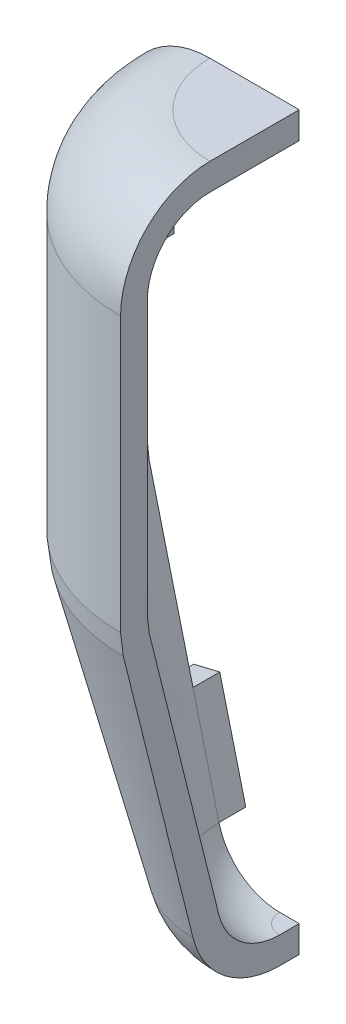
SolidWorks part; units mm, degrees
ref_plane "Front Plane" through (0, 0, 0) normal (0, 0, 1) x (1, 0, 0)
ref_plane "Top Plane" through (0, 0, 0) normal (0, 1, 0) x (1, 0, 0)
ref_plane "Right Plane" through (0, 0, 0) normal (1, 0, 0) x (0, 0, -1)
sketch "Sketch1" plane through (0, 0, 0) normal (0, 0, 1) x (1, 0, 0)
  line L0 (-55.7937, -33.3754) -> (-63.6014, -2.1443)
  line L1 (-63.9, 0.2811) -> (-63.9, 30.95)
  line L2 (-63.9, 30.95) -> (-60.9, 30.95) construction
  line L3 (-63.6014, -2.1443) -> (-63.9, 0.2811)
  line L5 (-53.9, 40.95) -> (-43.9, 40.95)
  line L6 (53.9, 40.95) -> (-53.9, 40.95) construction
  line L7 (-43.9, 40.95) -> (-43.9, 37.95)
  line L8 (-55.7937, -21.006) -> (-52.8832, -32.6477) construction
  line L9 (-52.8832, -32.6477) -> (-55.7937, -21.006)
  line L10 (-55.7937, -21.006) -> (-60.691, -1.4167)
  line L11 (-43.9, 37.95) -> (-53.9, 37.95)
  line L12 (-60.9, 30.95) -> (-60.9, 0.2811)
  line L13 (-60.9, 0.2811) -> (-60.691, -1.4167)
  line L14 (-43.9, -40.95) -> (-46.0922, -40.95)
  line L15 (46.0922, -40.95) -> (-46.0922, -40.95) construction
  line L16 (-43.9, -40.95) -> (-43.9, -37.95)
  line L17 (-43.9, -37.95) -> (-46.0922, -37.95)
  arc A0 (-53.9, 40.95) -> (-63.9, 30.95) centre (-53.9, 30.95) ccw construction
  arc A1 (-63.9, 30.95) -> (-53.9, 40.95) centre (-53.9, 30.95) cw
  arc A2 (-55.7937, -33.3754) -> (-46.0922, -40.95) centre (-46.0922, -30.95) ccw
  arc A3 (-55.7937, -33.3754) -> (-46.0922, -40.95) centre (-46.0922, -30.95) ccw construction
  arc A4 (-46.0922, -37.95) -> (-52.8832, -32.6477) centre (-46.0922, -30.95) cw
  arc A5 (-53.9, 37.95) -> (-60.9, 30.95) centre (-53.9, 30.95) ccw
  dimension "D1" = 10
  dimension "D2" = 3
revolve "Revolve2" add sketch "Sketch1" angle 90 about L7
sketch "Sketch3" plane through (0, 0, 0) normal (0, 0, -1) x (-1, 0, 0)
  line L0 (60.9, 0.2811) -> (60.9, 30.95) construction
  line L1 (60.9, 18.95) -> (63.9, 18.95)
  line L2 (60.9, 18.95) -> (60.9, 30.95)
  line L3 (60.9, 30.95) -> (63.9, 30.95)
  line L4 (63.9, 18.95) -> (63.9, 30.95)
  line L5 (60.9, 18.95) -> (63.9, 18.95) construction
  line L6 (58.7117, -21.7033) -> (55.7937, -33.3754)
  line L7 (63.6014, -2.1443) -> (55.7937, -33.3754) construction
  line L8 (55.7937, -33.3754) -> (52.8832, -32.6477)
  line L9 (52.8832, -32.6477) -> (55.7937, -21.006)
  line L10 (52.8832, -32.6477) -> (60.691, -1.4167) construction
  line L11 (55.7937, -21.006) -> (58.7117, -21.7033)
  line M6 (60.9, 30.95) -> (60.9, 0.2811)
  line M8 (60.691, -1.4167) -> (52.8832, -32.6477)
  line M14 (55.7937, -33.3754) -> (63.6014, -2.1443)
  line M16 (63.9, 0.2811) -> (63.9, 30.95)
extrude "Boss-Extrude1" add sketch "Sketch3" along normal up to surface (3 mm away) contours L11 L8 M8 M14 | L3 L1 M6 M16
